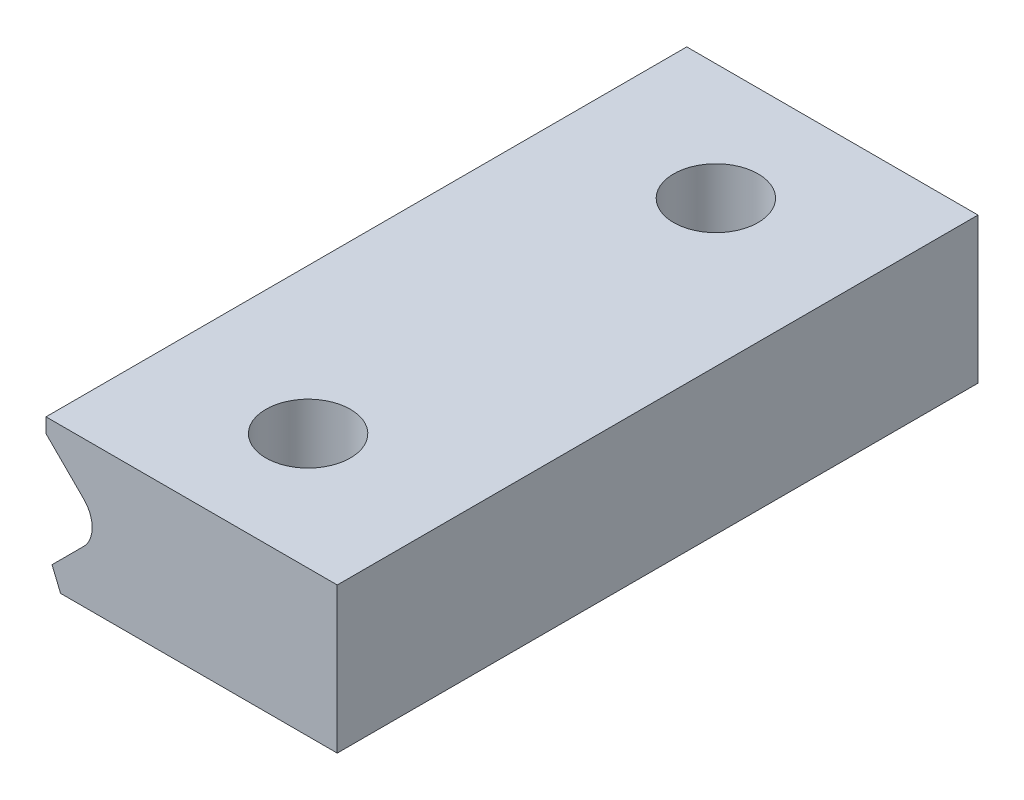
SolidWorks part; units mm, degrees
material "AISI Type 316L stainless steel"
ref_plane "Front Plane" through (0, 0, 0) normal (0, 0, 1) x (1, 0, 0)
ref_plane "Top Plane" through (0, 0, 0) normal (0, 1, 0) x (1, 0, 0)
ref_plane "Right Plane" through (0, 0, 0) normal (1, 0, 0) x (0, 0, -1)
sketch "Sketch1" plane through (0, 0, 0) normal (0, 0, 1) x (1, 0, 0)
  line L0 (-10.5, 2.5) -> (-8, 0)
  line L3 (-10.5, -2.5) -> (-8, 0)
  line L5 (55, 0) -> (-55, 0) construction
  line L6 (-10.5, 2.5) -> (0, 2.5)
  line L7 (-10.5, -2.5) -> (0, -2.5)
  line L8 (0, 2.5) -> (0, -2.5)
  dimension "D1" = 10.5
  dimension "D2" = 90
  dimension "D3" = 5
extrude "Boss-Extrude1" add sketch "Sketch1" along normal mid plane 22
fillet "Fillet1" radius 1 1 edges at (-8, 0, 0)
chamfer "Chamfer1" distance 1 1 edges at (-10.5, -2.5, 0)
sketch "Sketch2" plane through (0, 0, 11) normal (0, 0, 1) x (1, 0, 0)
  line L0 (-10, 2) -> (-10, 2.5)
  line L1 (-10.5, 2.5) -> (-8.7071, 0.7071) construction
  line L2 (0, 2.5) -> (-10.5, 2.5) construction
  line L3 (0, -2.75) -> (0, 2.75) construction
  line L5 (10, 2) -> (10, 2.5)
  line L11 (0, -2.5) -> (0, 2.5)
  line L12 (0, -2.5) -> (0, 2.5)
  line L14 (-9.5, -2.5) -> (0, -2.5)
  line L18 (0, 2.5) -> (-10.5, 2.5)
  line L19 (-10.5, 2.5) -> (-8.7071, 0.7071)
  line L20 (-8.7071, -0.7071) -> (-9.7929, -1.7929)
  line L21 (-9.7929, -1.7929) -> (-9.5, -2.5)
  line L22 (-9.5, -2.5) -> (0, -2.5)
  line L26 (0, 2.5) -> (-10.5, 2.5)
  line L27 (-10.5, 2.5) -> (-8.7071, 0.7071)
  line L28 (-8.7071, -0.7071) -> (-9.7929, -1.7929)
  line L29 (-9.7929, -1.7929) -> (-9.5, -2.5)
  arc A3 (-8.7071, -0.7071) -> (-8.7071, 0.7071) centre (-9.4142, 0) ccw
  arc A5 (-8.7071, -0.7071) -> (-8.7071, 0.7071) centre (-9.4142, 0) ccw
  line M6 (0, 2.5) -> (-10.5, 2.5)
  line M7 (-10.5, 2.5) -> (-8.7071, 0.7071)
  dimension "D1" = 0.5
  dimension "D2" = 0
extrude "Cut-Extrude1" cut sketch "Sketch2" against normal through all contours L0 M7 M6
sketch "Sketch3" plane through (0, -2.5, 0) normal (0, -1, 0) x (1, 0, 0)
  line L0 (0, -2.75) -> (0, 2.75) construction
  line L1 (2.75, 0) -> (-2.75, 0) construction
  point P0 (-5, 7)
  point P3 (5, 7)
  point P6 (5, -7)
  point P7 (-5, -7)
  dimension "D1" = 10
  dimension "D2" = 14
hole_wizard "CSK for M2.5 Cross recessed raised CTSK head wood screws1" positions "3DSketch1" profile "Sketch4" countersink size "M2.5" standard "GB" end condition through all
sketch3d "3DSketch1"
  point P0 (-5, -2.5, 7)
  point P6 (-5, -2.5, -7)
sketch "Sketch4" plane through (-5, -2.5, 7) normal (1, 0, 0) x (0, 0, -1)
  line L0 (0, 0) -> (0, 5)
  line L1 (0, 5) -> (1.45, 5)
  line L2 (1.45, 5) -> (1.45, 1.25)
  line L3 (1.45, 1.25) -> (2.7, 0)
  line L5 (2.7, 0) -> (0, 0)
  line L6 (-1.45, 1.25) -> (-2.7, 0) construction
  line L11 (0, -6.35) -> (0, 107.95) construction
  dimension "Thru Hole Dia." = 2.9
  dimension "Thru Hole Depth" = 5
  dimension "Near C'Sink Dia." = 5.4
  dimension "Near C'Sink Angle" = 90
sketch "Sketch5" plane through (0, -2.5, 0) normal (0, -1, 0) x (1, 0, 0)
  point P0 (0, 0)
